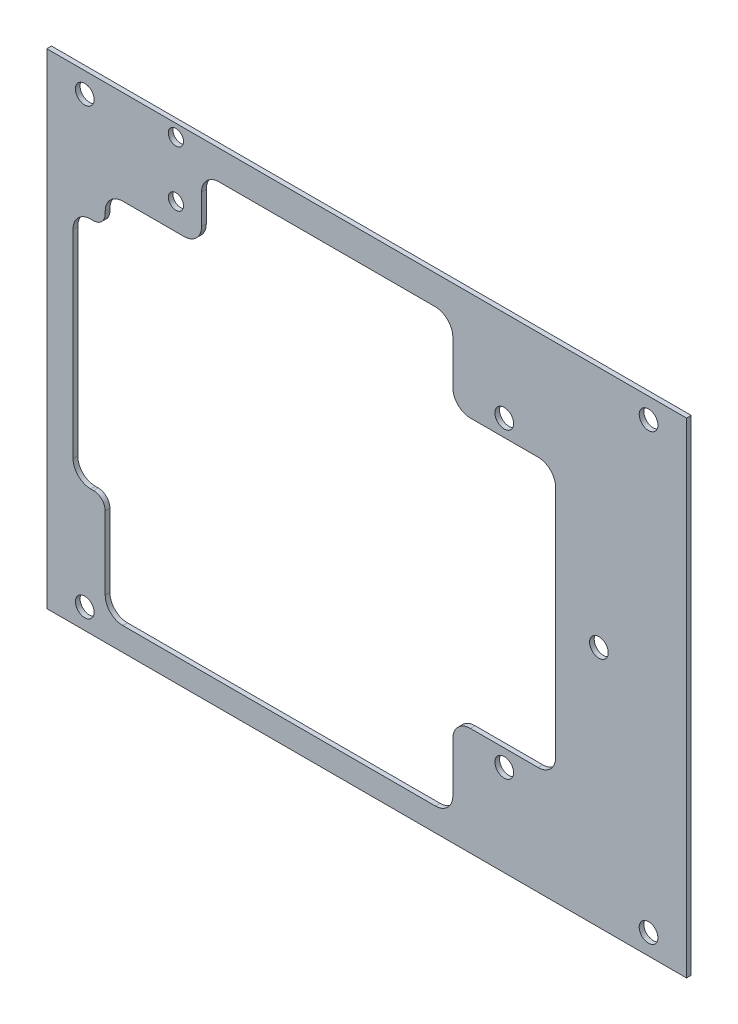
SolidWorks part; units mm, degrees
ref_plane "Front Plane" through (0, 0, 0) normal (0, 0, 1) x (1, 0, 0)
ref_plane "Top Plane" through (0, 0, 0) normal (0, 1, 0) x (1, 0, 0)
ref_plane "Right Plane" through (0, 0, 0) normal (1, 0, 0) x (0, 0, -1)
sketch "Sketch1" plane through (0, 0, 0) normal (0, 0, 1) x (1, 0, 0)
  line L0 (-50.25, -41.5) -> (-50.25, -61.5)
  line L1 (54.75, -83) -> (-54.75, -83)
  line L2 (54.75, -83) -> (54.75, 0)
  line L3 (54.75, 0) -> (-54.75, 0)
  line L4 (-54.75, -83) -> (-54.75, 0)
  line L5 (32.35, -18.5) -> (14.75, -18.5)
  line L6 (32.35, -64.5) -> (32.35, -18.5)
  line L7 (32.35, -64.5) -> (14.75, -64.5)
  line L8 (4.75, -41.5) -> (-54.75, -41.5) construction
  line L9 (-28.25, -5) -> (-28.25, -16.1)
  line L10 (-28.25, -16.1) -> (-44.75, -16.1)
  line L11 (-44.75, -16.1) -> (-44.75, -21.5)
  line L12 (-44.75, -79) -> (14.75, -79)
  line L13 (-50.25, -61.5) -> (-44.75, -61.5)
  line L14 (-44.75, -21.5) -> (-50.25, -21.5)
  line L15 (14.75, -18.5) -> (14.75, -5)
  line L16 (-50.25, -21.5) -> (-50.25, -41.5)
  line L17 (14.75, -64.5) -> (14.75, -79)
  line L18 (14.75, -5) -> (-28.25, -5)
  line L19 (-44.75, -61.5) -> (-44.75, -79)
  circle A0 centre (23.55, -67.375) radius 1.6
  circle A1 centre (23.55, -15.625) radius 1.6
  circle A2 centre (48.25, -3.5) radius 1.6
  circle A3 centre (48.25, -79.5) radius 1.6
  circle A4 centre (-48.25, -79.5) radius 1.6
  circle A5 centre (-48.25, -3.5) radius 1.6
  circle A6 centre (-32.65, -2.07) radius 1.3
  circle A7 centre (-32.65, -11.6) radius 1.3
  circle A8 centre (39.75, -41.5) radius 1.6
  dimension "D13" = 3.2
  dimension "D14" = 3.2
  dimension "D15" = 3.2
  dimension "D16" = 3.2
  dimension "D17" = 3.2
  dimension "D18" = 3.2
  dimension "D19" = 2.6
  dimension "D20" = 2.6
  dimension "D21" = 3.2
  dimension "D2" = 40
  dimension "D3" = 4
  dimension "D4" = 18.5
  dimension "D5" = 5
  dimension "D6" = 22.4
  dimension "D7" = 18.5
  dimension "D8" = 5.5
  dimension "D9" = 16.5
  dimension "D10" = 16.1
  dimension "D11" = 20
  dimension "D12" = 10
extrude "Boss-Extrude1" add sketch "Sketch1" along normal blind 0.8
fillet "Fillet1" radius 3 12 edges at (32.35, -18.5, 0.4) (14.75, -18.5, 0.4) (14.75, -5, 0.4) (-28.25, -5, 0.4) (-28.25, -16.1, 0.4) (-44.75, -16.1, 0.4) (-44.75, -79, 0.4) (14.75, -79, 0.4) (14.75, -64.5, 0.4) (32.35, -64.5, 0.4) (-50.25, -61.5, 0.4) (-50.25, -21.5, 0.4)
fillet "Fillet2" radius 2 2 edges at (-44.75, -61.5, 0.4) (-44.75, -21.5, 0.4)
